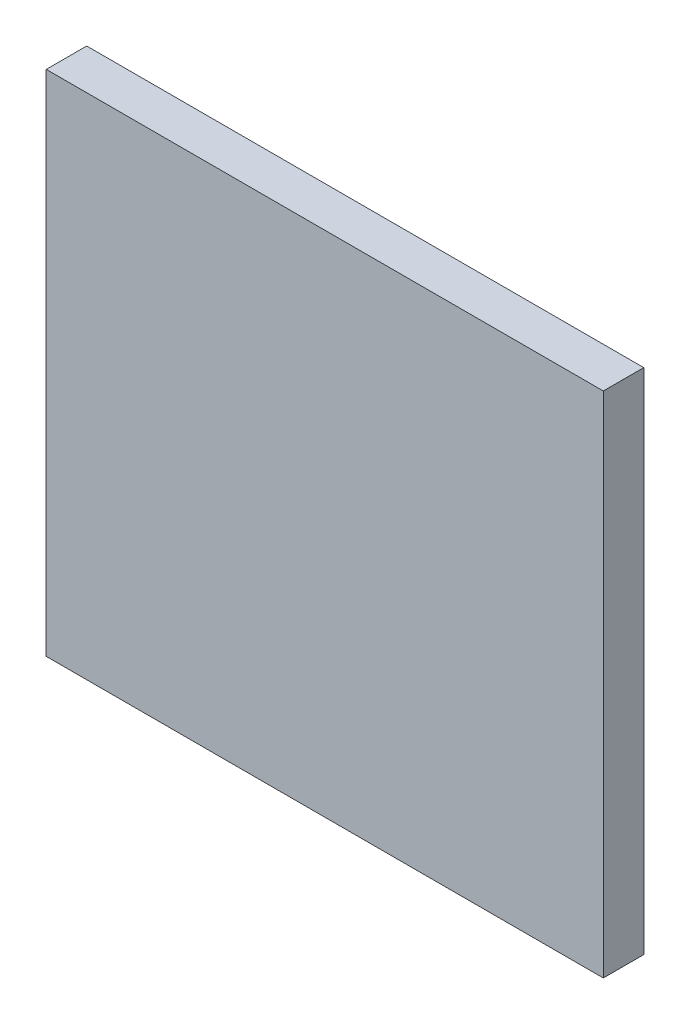
SolidWorks part; units mm, degrees
ref_plane "Front Plane" through (0, 0, 0) normal (0, 0, 1) x (1, 0, 0)
ref_plane "Top Plane" through (0, 0, 0) normal (0, 1, 0) x (1, 0, 0)
ref_plane "Right Plane" through (0, 0, 0) normal (1, 0, 0) x (0, 0, -1)
sketch "Sketch1" plane through (0, 0, 0) normal (0, 0, 1) x (1, 0, 0)
  line L1 (-17.6428, 15.8384) -> (23.6574, 15.8384)
  line L2 (-17.6428, 15.8384) -> (-17.6428, -21.853)
  line L3 (-17.6428, -21.853) -> (23.6574, -21.853)
  line L4 (23.6574, 15.8384) -> (23.6574, -21.853)
extrude "Boss-Extrude1" add sketch "Sketch1" along normal blind 3
